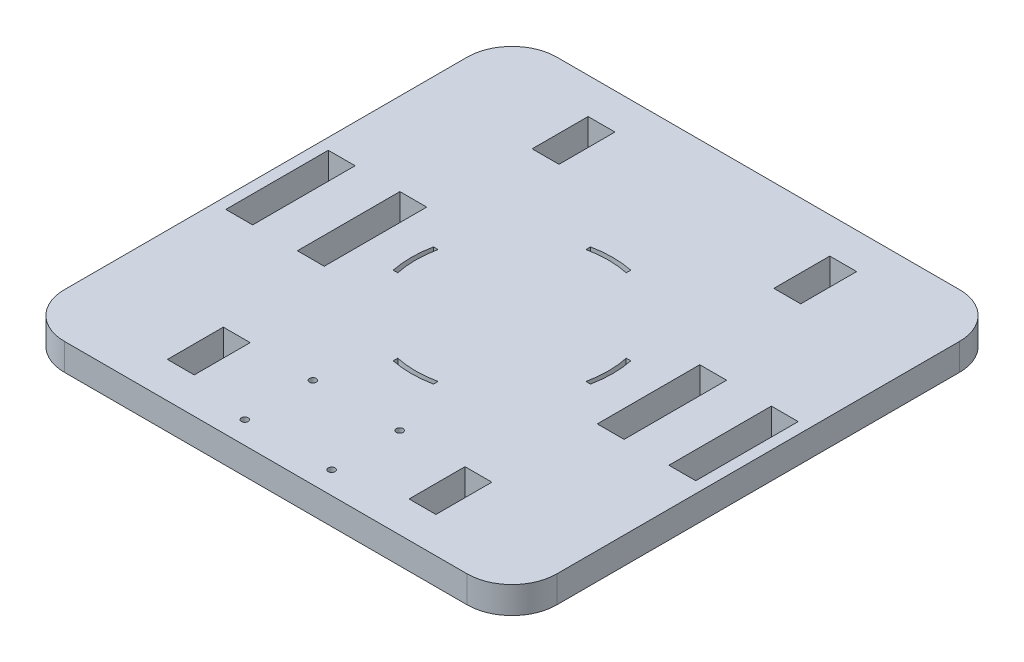
SolidWorks part; units mm, degrees
ref_plane "Front Plane" through (0, 0, 0) normal (0, 0, 1) x (1, 0, 0)
ref_plane "Top Plane" through (0, 0, 0) normal (0, 1, 0) x (1, 0, 0)
ref_plane "Right Plane" through (0, 0, 0) normal (1, 0, 0) x (0, 0, -1)
sketch "Sketch1" plane through (0, 0, 0) normal (0, 1, 0) x (1, 0, 0)
  line L1 (0, 0) -> (279.4, 0)
  line L2 (0, 0) -> (0, 279.4)
  line L3 (0, 279.4) -> (279.4, 279.4)
  line L4 (279.4, 0) -> (279.4, 279.4)
  dimension "D1" = 279.4
  dimension "D2" = 279.4
extrude "Boss-Extrude1" add sketch "Sketch1" along normal blind 15.24
fillet "Fillet1" radius 25.4 4 edges at (0, 7.62, -279.4) (0, 7.62, 0) (279.4, 7.62, 0) (279.4, 7.62, -279.4)
sketch "Sketch2" plane through (0, 15.24, 0) normal (0, 1, 0) x (1, 0, 0)
  line L0 (254, 279.4) -> (25.4, 279.4) construction
  line L1 (63.5, 259.08) -> (78.74, 259.08)
  line L2 (63.5, 259.08) -> (63.5, 227.33)
  line L3 (63.5, 227.33) -> (78.74, 227.33)
  line L4 (78.74, 259.08) -> (78.74, 227.33)
  line L5 (200.66, 259.08) -> (215.9, 259.08)
  line L6 (200.66, 259.08) -> (200.66, 227.33)
  line L7 (200.66, 227.33) -> (215.9, 227.33)
  line L8 (215.9, 259.08) -> (215.9, 227.33)
  line L9 (63.5, 52.07) -> (78.74, 52.07)
  line L10 (63.5, 52.07) -> (63.5, 20.32)
  line L11 (63.5, 20.32) -> (78.74, 20.32)
  line L12 (78.74, 52.07) -> (78.74, 20.32)
  line L13 (200.66, 52.07) -> (215.9, 52.07)
  line L14 (200.66, 52.07) -> (200.66, 20.32)
  line L15 (200.66, 20.32) -> (215.9, 20.32)
  line L16 (215.9, 52.07) -> (215.9, 20.32)
  line L17 (25.4, 0) -> (254, 0) construction
  line L18 (0, 254) -> (0, 25.4) construction
  line L19 (279.4, 25.4) -> (279.4, 254) construction
  point P18 (71.12, 20.32)
  dimension "D1" = 15.24
  dimension "D2" = 15.24
  dimension "D3" = 15.24
  dimension "D4" = 15.24
  dimension "D5" = 20.32
  dimension "D6" = 20.32
  dimension "D7" = 20.32
  dimension "D8" = 20.32
  dimension "D9" = 31.75
  dimension "D10" = 31.75
  dimension "D11" = 31.75
  dimension "D12" = 31.75
  dimension "D13" = 63.5
  dimension "D14" = 63.5
  dimension "D15" = 63.5
  dimension "D16" = 63.5
extrude "Cut-Extrude1" cut sketch "Sketch2" against normal through all
sketch "Sketch3" plane through (0, 15.24, 0) normal (0, 1, 0) x (1, 0, 0)
  line L0 (279.4, 25.4) -> (279.4, 254) construction
  line L1 (6.35, 168.783) -> (21.59, 168.783)
  line L2 (6.35, 168.783) -> (6.35, 110.617)
  line L3 (6.35, 110.617) -> (21.59, 110.617)
  line L4 (21.59, 168.783) -> (21.59, 110.617)
  line L5 (257.81, 168.783) -> (273.05, 168.783)
  line L6 (257.81, 168.783) -> (257.81, 110.617)
  line L7 (257.81, 110.617) -> (273.05, 110.617)
  line L8 (273.05, 168.783) -> (273.05, 110.617)
  line L9 (46.99, 168.783) -> (62.23, 168.783)
  line L10 (46.99, 168.783) -> (46.99, 110.617)
  line L11 (46.99, 110.617) -> (62.23, 110.617)
  line L12 (62.23, 168.783) -> (62.23, 110.617)
  line L13 (217.17, 168.783) -> (232.41, 168.783)
  line L14 (217.17, 168.783) -> (217.17, 110.617)
  line L15 (217.17, 110.617) -> (232.41, 110.617)
  line L16 (232.41, 168.783) -> (232.41, 110.617)
  line L17 (0, 254) -> (0, 25.4) construction
  line L18 (254, 279.4) -> (25.4, 279.4) construction
  point P20 (13.97, 110.617)
  dimension "D1" = 15.24
  dimension "D2" = 15.24
  dimension "D3" = 15.24
  dimension "D4" = 15.24
  dimension "D5" = 25.4
  dimension "D6" = 25.4
  dimension "D7" = 6.35
  dimension "D8" = 6.35
  dimension "D9" = 58.166
  dimension "D10" = 58.166
  dimension "D13" = 110.617
  dimension "D14" = 110.617
  dimension "D15" = 110.617
  dimension "D16" = 110.617
extrude "Cut-Extrude2" cut sketch "Sketch3" against normal through all
sketch "Sketch5" plane through (0, 0, 0) normal (0, -1, 0) x (1, 0, 0)
  line L0 (25.4, 0) -> (254, 0) construction
  line L1 (0, -254) -> (0, -25.4) construction
  circle A0 centre (115.062, -12.7) radius 1.905
  circle A1 centre (164.338, -12.7) radius 1.905
  circle A2 centre (164.338, -51.308) radius 1.905
  circle A3 centre (115.062, -51.308) radius 1.905
  dimension "D1" = 3.81
  dimension "D2" = 3.81
  dimension "D3" = 3.81
  dimension "D4" = 3.81
  dimension "D5" = 49.276
  dimension "D6" = 49.276
  dimension "D7" = 38.608
  dimension "D8" = 12.7
  dimension "D9" = 12.7
  dimension "D10" = 38.608
  dimension "D11" = 115.062
  dimension "D12" = 115.062
extrude "Cut-Extrude4" cut sketch "Sketch5" against normal through all
sketch "Sketch6" plane through (0, 15.24, 0) normal (0, 1, 0) x (1, 0, 0)
  line L0 (254, 279.4) -> (25.4, 279.4) construction
  line L1 (0, 254) -> (0, 25.4) construction
  line L2 (83.7047, 128.27) -> (86.2996, 128.27)
  line L3 (86.2996, 151.13) -> (83.7047, 151.13)
  line L4 (128.27, 193.1004) -> (128.27, 195.6953)
  line L5 (151.13, 193.1004) -> (151.13, 195.6953)
  line L6 (193.1004, 128.27) -> (195.6953, 128.27)
  line L7 (193.1004, 151.13) -> (195.6953, 151.13)
  line L8 (151.13, 86.2996) -> (151.13, 83.7047)
  line L9 (128.27, 83.7047) -> (128.27, 86.2996)
  circle A0 centre (139.7, 139.7) radius 57.15 construction
  circle A1 centre (139.7, 139.7) radius 54.61 construction
  arc A2 (83.7047, 151.13) -> (83.7047, 128.27) centre (139.7, 139.7) ccw
  arc A3 (86.2996, 151.13) -> (86.2996, 128.27) centre (139.7, 139.7) ccw
  arc A4 (128.27, 193.1004) -> (151.13, 193.1004) centre (139.7, 139.7) cw
  arc A5 (128.27, 195.6953) -> (151.13, 195.6953) centre (139.7, 139.7) cw
  arc A6 (193.1004, 151.13) -> (193.1004, 128.27) centre (139.7, 139.7) cw
  arc A7 (195.6953, 151.13) -> (195.6953, 128.27) centre (139.7, 139.7) cw
  arc A8 (128.27, 86.2996) -> (151.13, 86.2996) centre (139.7, 139.7) ccw
  arc A9 (128.27, 83.7047) -> (151.13, 83.7047) centre (139.7, 139.7) ccw
  dimension "D3" = 114.3
  dimension "D1" = 139.7
  dimension "D2" = 139.7
  dimension "D4" = 2.54
  dimension "D5" = 11.43
  dimension "D6" = 22.86
  dimension "D7" = 11.43
  dimension "D8" = 22.86
  dimension "D9" = 11.43
  dimension "D10" = 11.43
  dimension "D11" = 22.86
  dimension "D12" = 22.86
  dimension "D13" = 11.43
  dimension "D14" = 11.43
  dimension "D15" = 22.86
  dimension "D16" = 22.86
  dimension "D17" = 11.43
  dimension "D18" = 11.43
  dimension "D19" = 22.86
  dimension "D20" = 22.86
extrude "Cut-Extrude5" cut sketch "Sketch6" against normal through all
equation "\"MDF\"= .3"
equation "\"Foamcore\"= .1"
equation "\"GMaterial\"= .6"
equation "\"D1@Boss-Extrude1\"=\"GMaterial\""
equation "\"D2@Sketch2\"=\"GMaterial\""
equation "\"D1@Sketch2\"=\"GMaterial\""
equation "\"D4@Sketch2\"=\"GMaterial\""
equation "\"D3@Sketch2\"=\"GMaterial\""
equation "\"D3@Sketch3\"=\"GMaterial\""
equation "\"D4@Sketch3\"=\"GMaterial\""
equation "\"D2@Sketch3\"=\"GMaterial\""
equation "\"D1@Sketch3\"=\"GMaterial\""
equation "\"D4@Sketch6\"=\"Foamcore\""
